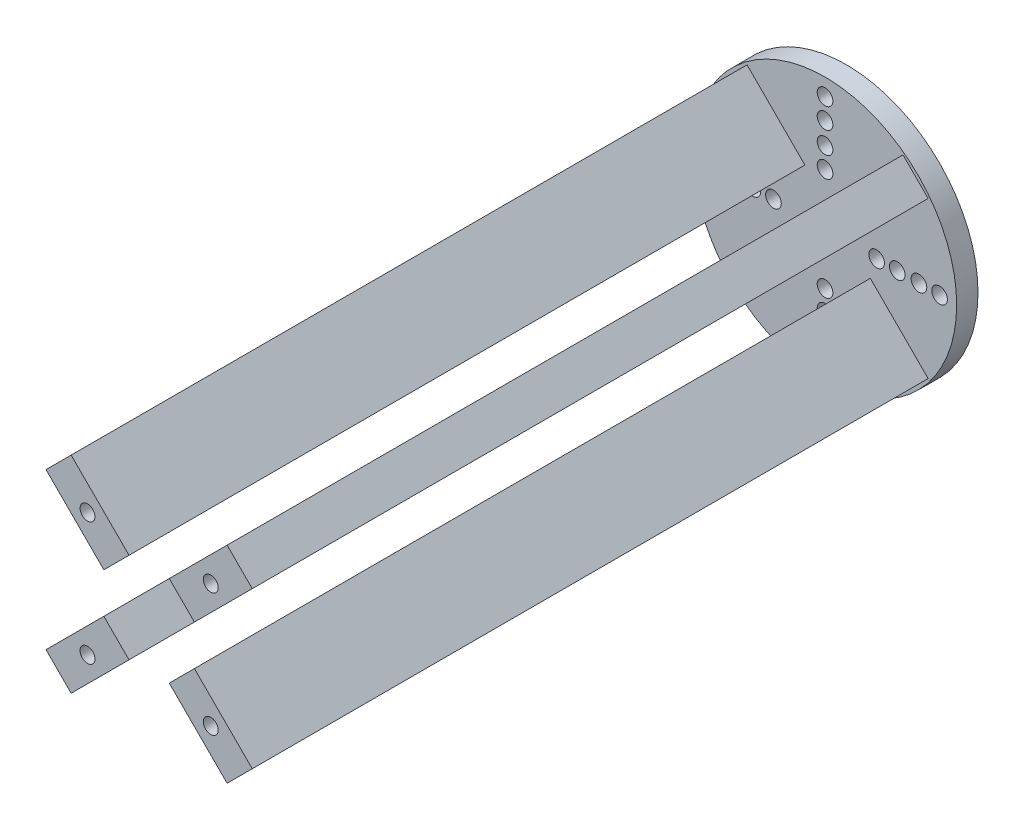
SolidWorks part; units mm, degrees
ref_plane "Ebene vorne" through (0, 0, 0) normal (0, 0, 1) x (1, 0, 0)
ref_plane "Ebene oben" through (0, 0, 0) normal (0, 1, 0) x (1, 0, 0)
ref_plane "Ebene rechts" through (0, 0, 0) normal (1, 0, 0) x (0, 0, -1)
sketch "Skizze2" plane through (0, 0, 0) normal (0, 0, 1) x (1, 0, 0)
  line L0 (0, 18.5) -> (0, -18.5)
  line L1 (-18.5, 0) -> (18.5, 0)
  circle A0 centre (0, 0) radius 18.5
  arc A1 (16.0624, -1.0994) -> (16.0624, 1.0994) centre (0, 0) ccw
  arc A2 (13.1542, -1.099) -> (13.1542, 1.099) centre (0, 0) ccw
  arc A3 (10.0904, -1.0984) -> (10.0904, 1.0984) centre (0, 0) ccw
  arc A4 (7.1666, -1.0968) -> (7.1666, 1.0968) centre (0, 0) ccw
  circle A5 centre (0, 7.25) radius 1.1
  circle A6 centre (0, 10.15) radius 1.1
  circle A7 centre (0, 13.2) radius 1.1
  circle A8 centre (0, 16.1) radius 1.1
  circle A9 centre (7.25, 0) radius 1.1
  circle A10 centre (10.15, 0) radius 1.1
  circle A11 centre (13.2, 0) radius 1.1
  circle A12 centre (16.1, 0) radius 1.1
  circle A13 centre (0, -7.25) radius 1.1
  circle A14 centre (0, -10.15) radius 1.1
  circle A15 centre (0, -13.2) radius 1.1
  circle A16 centre (0, -16.1) radius 1.1
  circle A17 centre (-7.25, 0) radius 1.1
  circle A18 centre (-10.15, 0) radius 1.1
  circle A19 centre (-13.2, 0) radius 1.1
  circle A20 centre (-16.1, 0) radius 1.1
  arc A21 (1.0968, 7.1666) -> (-1.0968, 7.1666) centre (0, 0) ccw
  arc A22 (1.0984, 10.0904) -> (-1.0984, 10.0904) centre (0, 0) ccw
  arc A23 (1.099, 13.1542) -> (-1.099, 13.1542) centre (0, 0) ccw
  arc A24 (1.0994, 16.0624) -> (-1.0994, 16.0624) centre (0, 0) ccw
  arc A25 (-7.1666, 1.0968) -> (-7.1666, -1.0968) centre (0, 0) ccw
  arc A26 (-10.0904, 1.0984) -> (-10.0904, -1.0984) centre (0, 0) ccw
  arc A27 (-13.1542, 1.099) -> (-13.1542, -1.099) centre (0, 0) ccw
  arc A28 (-16.0624, 1.0994) -> (-16.0624, -1.0994) centre (0, 0) ccw
  arc A29 (-1.0968, -7.1666) -> (1.0968, -7.1666) centre (0, 0) ccw
  arc A30 (-1.0984, -10.0904) -> (1.0984, -10.0904) centre (0, 0) ccw
  arc A31 (-1.099, -13.1542) -> (1.099, -13.1542) centre (0, 0) ccw
  arc A32 (-1.0994, -16.0624) -> (1.0994, -16.0624) centre (0, 0) ccw
  point P46 (0, 0)
  dimension "D1" = 37
  dimension "D2" = 32.2
  dimension "D3" = 26.4
  dimension "D4" = 20.3
  dimension "D5" = 14.5
  dimension "D6" = 2.2
  dimension "D7" = 4
extrude "Aufsatz-Linear austragen1" add sketch "Skizze2" along normal blind 3 contours A12 L1 A0 L0 A8 A7 A6 A5 A9 A10 A11 | A16 L0 A0 L1 A12 A11 A10 A9 A13 A14 A15 | A20 L1 A0 L0 A16 A15 A14 A13 A17 A18 A19 | A20 L1 A19 A18 A17 L0 A5 A6 A7 A8 A0
sketch "Skizze4" plane through (0, 0, 3) normal (0, 0, 1) x (1, 0, 0)
  line L0 (0, 0) -> (13.0815, 13.0815) construction
  line L1 (2.8284, 6.364) -> (10.9602, 14.4957)
  line L2 (2.8284, 6.364) -> (6.364, 2.8284)
  line L3 (10.9602, 14.4957) -> (14.4957, 10.9602)
  line L4 (6.364, 2.8284) -> (14.4957, 10.9602)
  line L5 (0, 0) -> (18.5, 0) construction
  line L6 (6.364, -2.8284) -> (14.4957, -10.9602)
  line L7 (6.364, -2.8284) -> (2.8284, -6.364)
  line L8 (2.8284, -6.364) -> (10.9602, -14.4957)
  line L9 (14.4957, -10.9602) -> (10.9602, -14.4957)
  line L10 (-2.8284, -6.364) -> (-10.9602, -14.4957)
  line L11 (-2.8284, -6.364) -> (-6.364, -2.8284)
  line L12 (-6.364, -2.8284) -> (-14.4957, -10.9602)
  line L13 (-10.9602, -14.4957) -> (-14.4957, -10.9602)
  line L14 (-6.364, 2.8284) -> (-14.4957, 10.9602)
  line L15 (-6.364, 2.8284) -> (-2.8284, 6.364)
  line L16 (-2.8284, 6.364) -> (-10.9602, 14.4957)
  line L17 (-14.4957, 10.9602) -> (-10.9602, 14.4957)
  circle A0 centre (0, 0) radius 18.5 construction
  point P26 (0, 0)
  dimension "D1" = 2.5
  dimension "D2" = 45
  dimension "D3" = 11.5
  dimension "D4" = 6.5
  dimension "D5" = 2.5
  dimension "D6" = 4
extrude "Aufsatz-Linear austragen2" add sketch "Skizze4" along normal blind 95
sketch "Skizze5" plane through (0, 0, 98) normal (0, 0, 1) x (1, 0, 0)
  line L0 (-6.364, -2.8284) -> (-10.9602, -14.4957) construction
  line L1 (-2.8284, -6.364) -> (-6.364, -2.8284) construction
  line L2 (-6.364, -2.8284) -> (-14.4957, -10.9602) construction
  line L3 (-10.9602, -14.4957) -> (-14.4957, -10.9602) construction
  line L4 (-2.8284, -6.364) -> (-14.4957, -10.9602) construction
  circle A0 centre (-8.6621, -8.6621) radius 1.05
  circle A1 centre (-8.6621, 8.6621) radius 1.05
  circle A2 centre (8.6621, 8.6621) radius 1.05
  circle A3 centre (8.6621, -8.6621) radius 1.05
  point P22 (0, 0)
  dimension "D1" = 2.1
  dimension "D2" = 4
extrude "Schnitt-Linear austragen2" cut sketch "Skizze5" against normal blind 13
